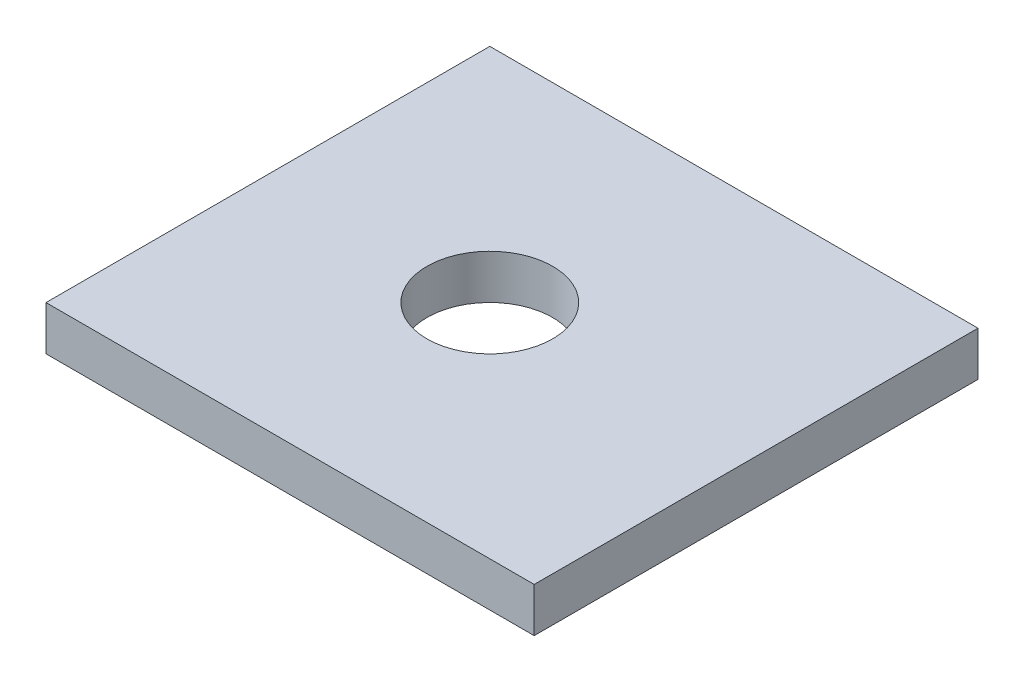
SolidWorks part; units mm, degrees
ref_plane "Alzado" through (0, 0, 0) normal (0, 0, 1) x (1, 0, 0)
ref_plane "Planta" through (0, 0, 0) normal (0, 1, 0) x (1, 0, 0)
ref_plane "Vista lateral" through (0, 0, 0) normal (1, 0, 0) x (0, 0, -1)
sketch "Croquis1" plane through (0, 0, 0) normal (0, 1, 0) x (1, 0, 0)
  line L1 (-16.5, 15) -> (16.5, 15)
  line L2 (-16.5, 15) -> (-16.5, -15)
  line L3 (-16.5, -15) -> (16.5, -15)
  line L4 (16.5, 15) -> (16.5, -15)
  line L5 (-16.5, 15) -> (16.5, -15) construction
  line L6 (-16.5, -15) -> (16.5, 15) construction
  point P0 (0, 0)
extrude "Saliente-Extruir1" add sketch "Croquis1" along normal blind 3
sketch "Croquis2" plane through (0, 3, 0) normal (0, 1, 0) x (1, 0, 0)
  line L0 (-16.5, 15) -> (-16.5, -15) construction
  line L1 (-16.5, -15) -> (16.5, -15) construction
  circle A0 centre (-1.5, 0) radius 4.25
  dimension "D1" = 15
  dimension "D2" = 15
extrude "Cortar-Extruir1" cut sketch "Croquis2" against normal blind 3
